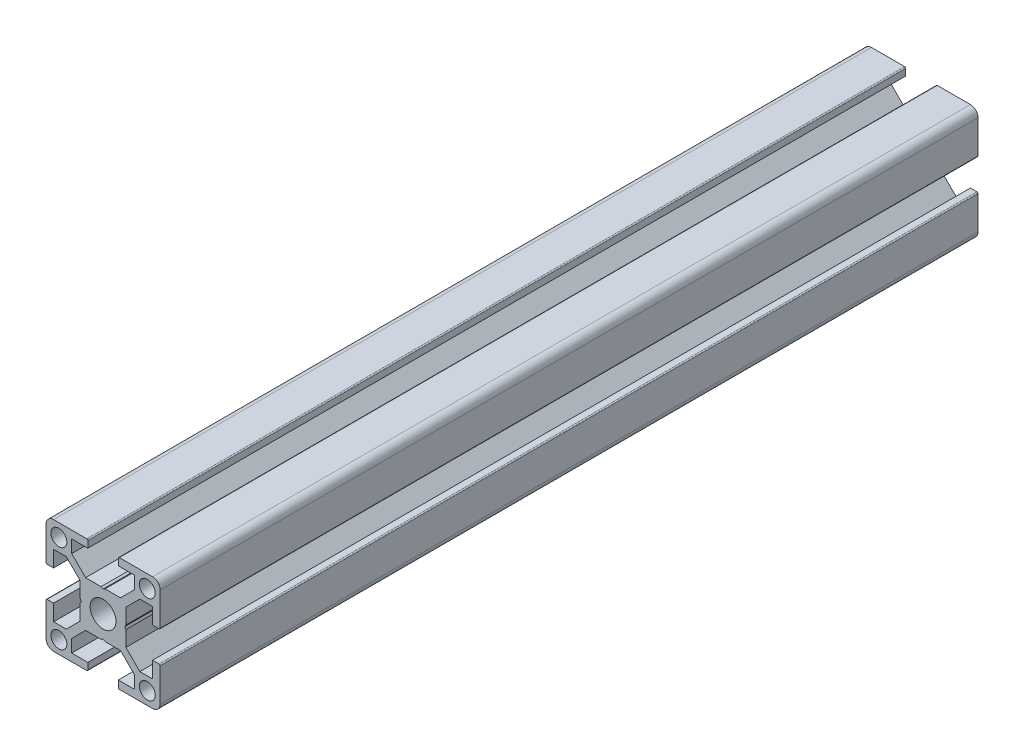
SolidWorks part; units mm, degrees
ref_plane "Front Plane" through (0, 0, 0) normal (0, 0, 1) x (1, 0, 0)
ref_plane "Top Plane" through (0, 0, 0) normal (0, 1, 0) x (1, 0, 0)
ref_plane "Right Plane" through (0, 0, 0) normal (1, 0, 0) x (0, 0, -1)
sketch "Sketch1" plane through (0, 0, 0) normal (0, 0, 1) x (1, 0, 0)
  line L0 (-14.7, 4) -> (-13, 4)
  line L1 (-13, 4) -> (-13, 8.25)
  line L2 (-13, 8.25) -> (-9.6642, 8.25)
  line L3 (-9.6642, 8.25) -> (-6, 4.5858)
  line L4 (-6, 4.5858) -> (-6, 0.5196)
  line L5 (-6, 0.5196) -> (-5.7, 0)
  line L6 (-5.7, 0) -> (-6, -0.5196)
  line L7 (-6, -0.5196) -> (-6, -4.5858)
  line L8 (-6, -4.5858) -> (-9.6642, -8.25)
  line L9 (-9.6642, -8.25) -> (-13, -8.25)
  line L10 (-13, -8.25) -> (-13, -4)
  line L11 (-13, -4) -> (-14.7, -4)
  line L12 (-15, -4.3) -> (-15, -13)
  line L13 (-13, -15) -> (-4.3, -15)
  line L14 (-4, -14.7) -> (-4, -13)
  line L15 (-4, -13) -> (-8.25, -13)
  line L16 (-8.25, -13) -> (-8.25, -9.6642)
  line L17 (-8.25, -9.6642) -> (-4.5858, -6)
  line L18 (-4.5858, -6) -> (-0.5196, -6)
  line L19 (-0.5196, -6) -> (0, -5.7)
  line L20 (0, -5.7) -> (0.5196, -6)
  line L21 (0.5196, -6) -> (4.5858, -6)
  line L22 (4.5858, -6) -> (8.25, -9.6642)
  line L23 (8.25, -9.6642) -> (8.25, -13)
  line L24 (8.25, -13) -> (4, -13)
  line L25 (4, -13) -> (4, -14.7)
  line L26 (4.3, -15) -> (13, -15)
  line L27 (15, -13) -> (15, -4.3)
  line L28 (14.7, -4) -> (13, -4)
  line L29 (13, -4) -> (13, -8.25)
  line L30 (13, -8.25) -> (9.6642, -8.25)
  line L31 (9.6642, -8.25) -> (6, -4.5858)
  line L32 (6, -4.5858) -> (6, -0.5196)
  line L33 (6, -0.5196) -> (5.7, 0)
  line L34 (5.7, 0) -> (6, 0.5196)
  line L35 (6, 0.5196) -> (6, 4.5858)
  line L36 (6, 4.5858) -> (9.6642, 8.25)
  line L37 (9.6642, 8.25) -> (13, 8.25)
  line L38 (13, 8.25) -> (13, 4)
  line L39 (13, 4) -> (14.7, 4)
  line L40 (15, 4.3) -> (15, 13)
  line L41 (13, 15) -> (4.3, 15)
  line L42 (4, 14.7) -> (4, 13)
  line L43 (4, 13) -> (8.25, 13)
  line L44 (8.25, 13) -> (8.25, 9.6642)
  line L45 (8.25, 9.6642) -> (4.5858, 6)
  line L46 (4.5858, 6) -> (0.5196, 6)
  line L47 (0.5196, 6) -> (0, 5.7)
  line L48 (0, 5.7) -> (-0.5196, 6)
  line L49 (-0.5196, 6) -> (-4.5858, 6)
  line L50 (-4.5858, 6) -> (-8.25, 9.6642)
  line L51 (-8.25, 9.6642) -> (-8.25, 13)
  line L52 (-8.25, 13) -> (-4, 13)
  line L53 (-4, 13) -> (-4, 14.7)
  line L54 (-4.3, 15) -> (-13, 15)
  line L55 (-15, 13) -> (-15, 4.3)
  arc A0 (-15, 4.3) -> (-14.7, 4) centre (-14.7, 4.3) ccw
  arc A1 (-14.7, -4) -> (-15, -4.3) centre (-14.7, -4.3) ccw
  arc A2 (-15, -13) -> (-13, -15) centre (-13, -13) ccw
  arc A3 (-4.3, -15) -> (-4, -14.7) centre (-4.3, -14.7) ccw
  arc A4 (4, -14.7) -> (4.3, -15) centre (4.3, -14.7) ccw
  arc A5 (13, -15) -> (15, -13) centre (13, -13) ccw
  arc A6 (15, -4.3) -> (14.7, -4) centre (14.7, -4.3) ccw
  arc A7 (14.7, 4) -> (15, 4.3) centre (14.7, 4.3) ccw
  arc A8 (15, 13) -> (13, 15) centre (13, 13) ccw
  arc A9 (4.3, 15) -> (4, 14.7) centre (4.3, 14.7) ccw
  arc A10 (-4, 14.7) -> (-4.3, 15) centre (-4.3, 14.7) ccw
  arc A11 (-13, 15) -> (-15, 13) centre (-13, 13) ccw
  circle A12 centre (11.625, 11.625) radius 2.1
  circle A13 centre (11.625, -11.625) radius 2.1
  circle A14 centre (0, 0) radius 3.4
  circle A15 centre (-11.625, -11.625) radius 2.1
  circle A16 centre (-11.625, 11.625) radius 2.1
extrude "Boss-Extrude1" add sketch "Sketch1" along normal blind 215
